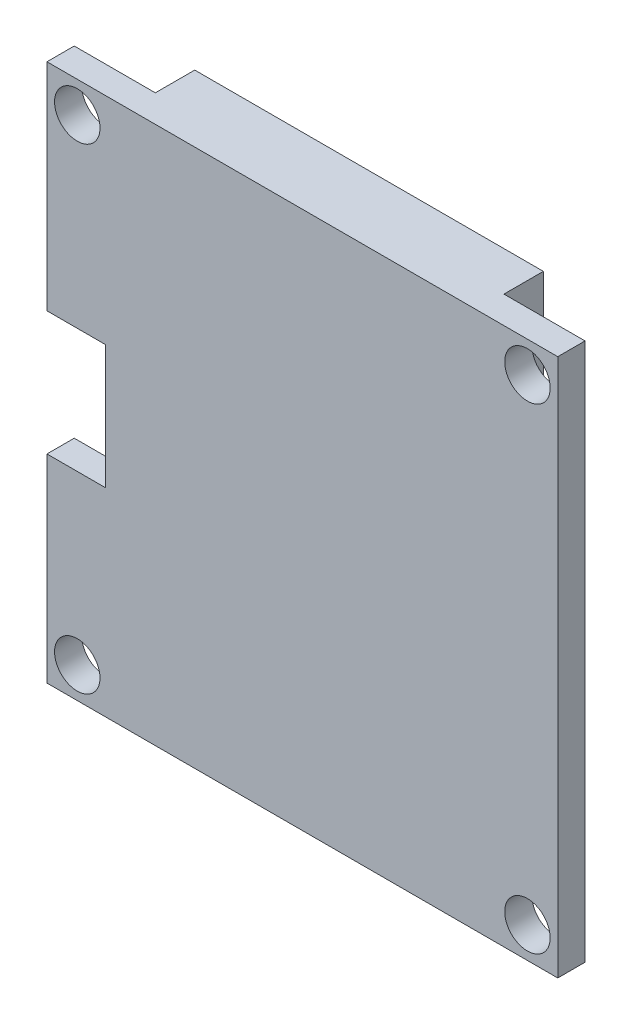
SolidWorks part; units mm, degrees
ref_plane "Front Plane" through (0, 0, 0) normal (0, 0, 1) x (1, 0, 0)
ref_plane "Top Plane" through (0, 0, 0) normal (0, 1, 0) x (1, 0, 0)
ref_plane "Right Plane" through (0, 0, 0) normal (1, 0, 0) x (0, 0, -1)
sketch "Sketch1" plane through (0, 0, 0) normal (0, 0, 1) x (1, 0, 0)
  line L0 (0, -15.71) -> (14.85, -15.71)
  line L5 (7.35, 14.71) -> (-7.35, 14.71)
  line L6 (7.35, 14.71) -> (7.35, -14.71)
  line L7 (7.35, -14.71) -> (-7.35, -14.71)
  line L8 (-7.35, 14.71) -> (-7.35, -14.71)
  line L9 (7.35, 14.71) -> (-7.35, -14.71) construction
  line L14 (7.35, -14.71) -> (-7.35, 14.71) construction
  line L15 (8.35, 15.71) -> (-8.35, 15.71) construction
  line L16 (8.35, 15.71) -> (8.35, -15.71) construction
  line L17 (8.35, -15.71) -> (-8.35, -15.71) construction
  line L18 (-8.35, 15.71) -> (-8.35, -15.71) construction
  line L19 (8.35, 15.71) -> (-8.35, -15.71) construction
  line L20 (8.35, -15.71) -> (-8.35, 15.71) construction
  line L21 (16.85, 17.75) -> (-16.85, 17.75)
  line L22 (16.85, 17.75) -> (16.85, -17.75)
  line L23 (16.85, -17.75) -> (-16.85, -17.75)
  line L24 (-16.85, 17.75) -> (-16.85, 3.5191)
  line L25 (16.85, 17.75) -> (-16.85, -17.75) construction
  line L26 (16.85, -17.75) -> (-16.85, 17.75) construction
  line L27 (0, 0) -> (7.35, 0)
  line L28 (7.35, 0) -> (0, 0)
  line L29 (0, 0) -> (0, -14.71)
  line L30 (-16.85, -17.75) -> (-16.85, -4.6572)
  line L31 (-16.85, -4.6572) -> (-12.9877, -4.6572)
  line L32 (-12.9877, -4.6572) -> (-12.9877, 3.5191)
  line L33 (-12.9877, 3.5191) -> (-16.85, 3.5191)
  line L34 (-16.85, 3.5191) -> (-16.85, 17.75)
  line L35 (-16.85, -4.6572) -> (-16.85, -17.75)
  line L37 (-11.5, -17.75) -> (11.5, -17.75)
  line L38 (-11.5, -17.75) -> (-11.5, 17.75)
  line L39 (-11.5, 17.75) -> (11.5, 17.75)
  line L40 (11.5, -17.75) -> (11.5, 17.75)
  line L41 (-11.5, -17.75) -> (11.5, 17.75) construction
  line L42 (-11.5, 17.75) -> (11.5, -17.75) construction
  circle A5 centre (14.85, -15.71) radius 1.5
  circle A6 centre (14.85, 15.71) radius 1.5
  circle A7 centre (-14.85, 15.71) radius 1.5
  circle A8 centre (-14.85, -15.71) radius 1.5
  point P0 (0, 0)
  point P6 (0, 0)
  point P11 (0, 0)
  dimension "D4" = 16.7
  dimension "D8" = 3
  dimension "D1" = 29.42
  dimension "D2" = 14.7
  dimension "D3" = 31.42
  dimension "D5" = 35.5
  dimension "D6" = 33.7
  dimension "D7" = 14.85
  dimension "D9" = 3.8623
  dimension "D10" = 8.1762
  dimension "D11" = 3.8623
  dimension "D12" = 35.5
  dimension "D13" = 23
extrude "Boss-Extrude5" add sketch "Sketch1" along normal blind 1.8
sketch "Sketch2" plane through (0, 0, 0) normal (0, 0, -1) x (-1, 0, 0)
  line L1 (11.5, -17.75) -> (-11.5, -17.75)
  line L2 (11.5, -17.75) -> (11.5, 17.75)
  line L3 (11.5, 17.75) -> (-11.5, 17.75)
  line L4 (-11.5, -17.75) -> (-11.5, 17.75)
  line L5 (11.5, -17.75) -> (-11.5, 17.75) construction
  line L6 (11.5, 17.75) -> (-11.5, -17.75) construction
  point P0 (0, 0)
  dimension "D1" = 35.5
  dimension "D2" = 23
extrude "Boss-Extrude7" add sketch "Sketch2" along normal blind 2.6
sketch "Sketch3" plane through (0, 0, 0) normal (0, 0, -1) x (-1, 0, 0)
  circle A0 centre (-14.7221, -5.6108) radius 0.5104
  circle A1 centre (-14.7221, -1.5509) radius 0.5809
  circle A2 centre (-14.7417, 2.5) radius 0.5251
  dimension "D1" = 1.0502
  dimension "D2" = 1.1618
  dimension "D3" = 1.0209
extrude "Cut-Extrude1" cut sketch "Sketch3" against normal blind 1
sketch "Sketch5" plane through (0, 0, 0) normal (0, 0, -1) x (-1, 0, 0)
  circle A2 centre (-14.6773, 5.7173) radius 0.52
extrude "Cut-Extrude5" cut sketch "Sketch5" against normal blind 1
